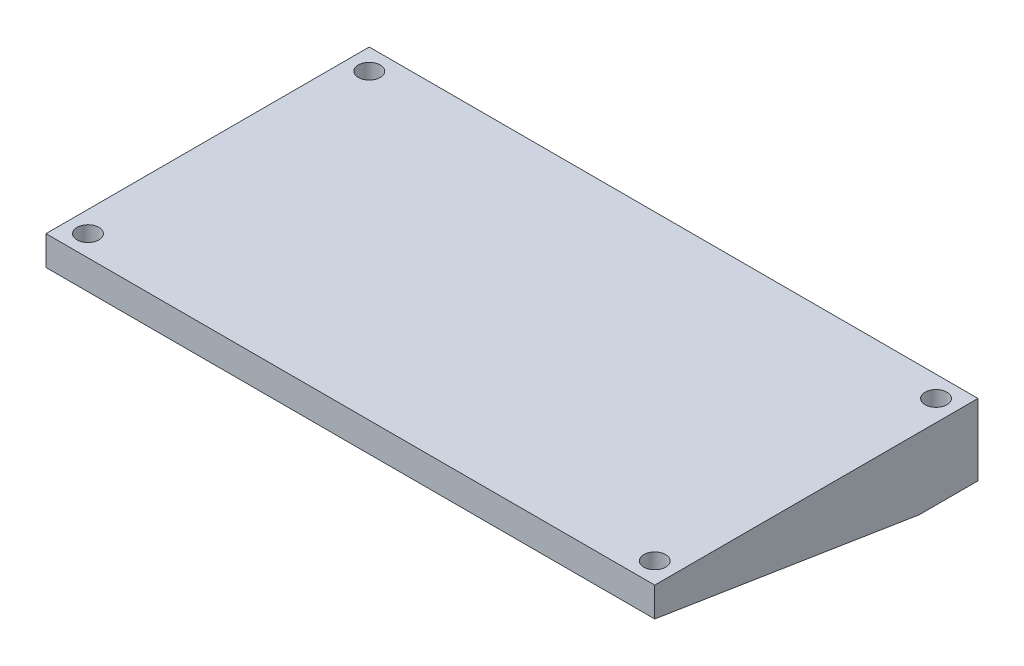
SolidWorks part; units mm, degrees
ref_plane "Front Plane" through (0, 0, 0) normal (0, 0, 1) x (1, 0, 0)
ref_plane "Top Plane" through (0, 0, 0) normal (0, 1, 0) x (1, 0, 0)
ref_plane "Right Plane" through (0, 0, 0) normal (1, 0, 0) x (0, 0, -1)
sketch "Sketch5" plane through (0, 0, 0) normal (0, 1, 0) x (1, 0, 0)
  line L5 (0, 0) -> (145, 0)
  line L6 (0, 0) -> (0, 77)
  line L7 (0, 77) -> (145, 77)
  line L8 (145, 0) -> (145, 77)
  dimension "D1" = 145
  dimension "D2" = 77
extrude "Boss-Extrude2" add sketch "Sketch5" along normal blind 17
chamfer "Chamfer2" distance 63 distance2 10 1 edges at (72.5, 0, 0)
sketch "Sketch1" plane through (0, 17, 0) normal (0, 1, 0) x (1, 0, 0)
  line L1 (0, 0) -> (145, 0)
  line L2 (0, 0) -> (0, 77)
  line L3 (0, 77) -> (145, 77)
  line L4 (145, 0) -> (145, 77)
  line L5 (50.91, 71.27) -> (94.09, 71.27)
  line L6 (50.91, 71.27) -> (50.91, 53.49)
  line L7 (50.91, 53.49) -> (94.09, 53.49)
  line L8 (94.09, 71.27) -> (94.09, 53.49)
  circle A0 centre (5, 72) radius 2.6
  circle A1 centre (5, 5) radius 2.6
  circle A2 centre (140, 5) radius 2.6
  circle A3 centre (140, 72) radius 2.6
  circle A4 centre (52.18, 70) radius 0.889
  circle A5 centre (52.18, 54.76) radius 0.889
  circle A6 centre (92.82, 54.76) radius 0.889
  circle A7 centre (92.82, 70) radius 0.889
  circle A8 centre (46.91, 70) radius 1.65
  circle A9 centre (46.91, 54.76) radius 1.65
  circle A10 centre (98.09, 70) radius 1.65
  circle A11 centre (98.09, 54.76) radius 1.65
  dimension "D1" = 5.2
  dimension "D2" = 5.2
  dimension "D3" = 5.2
  dimension "D12" = 5.2
  dimension "D27" = 1.778
  dimension "D28" = 1.778
  dimension "D29" = 1.778
  dimension "D30" = 1.778
  dimension "D32" = 3.3
  dimension "D33" = 3.3
  dimension "D35" = 3.3
  dimension "D36" = 3.3
  dimension "D4" = 5
  dimension "D5" = 5
  dimension "D6" = 5
  dimension "D7" = 5
  dimension "D8" = 5
  dimension "D9" = 5
  dimension "D10" = 5
  dimension "D11" = 5
  dimension "D13" = 145
  dimension "D14" = 77
  dimension "D15" = 17.78
  dimension "D16" = 43.18
  dimension "D17" = 7
  dimension "D18" = 50.91
  dimension "D19" = 1.27
  dimension "D20" = 1.27
  dimension "D21" = 1.27
  dimension "D22" = 1.27
  dimension "D23" = 1.27
  dimension "D24" = 1.27
  dimension "D25" = 1.27
  dimension "D26" = 1.27
  dimension "D31" = 4
  dimension "D34" = 4
  dimension "D37" = 4
  dimension "D38" = 4
extrude "Cut-Extrude1" cut sketch "Sketch1" against normal blind 5 contours A0 | A1 | A2 | A3
